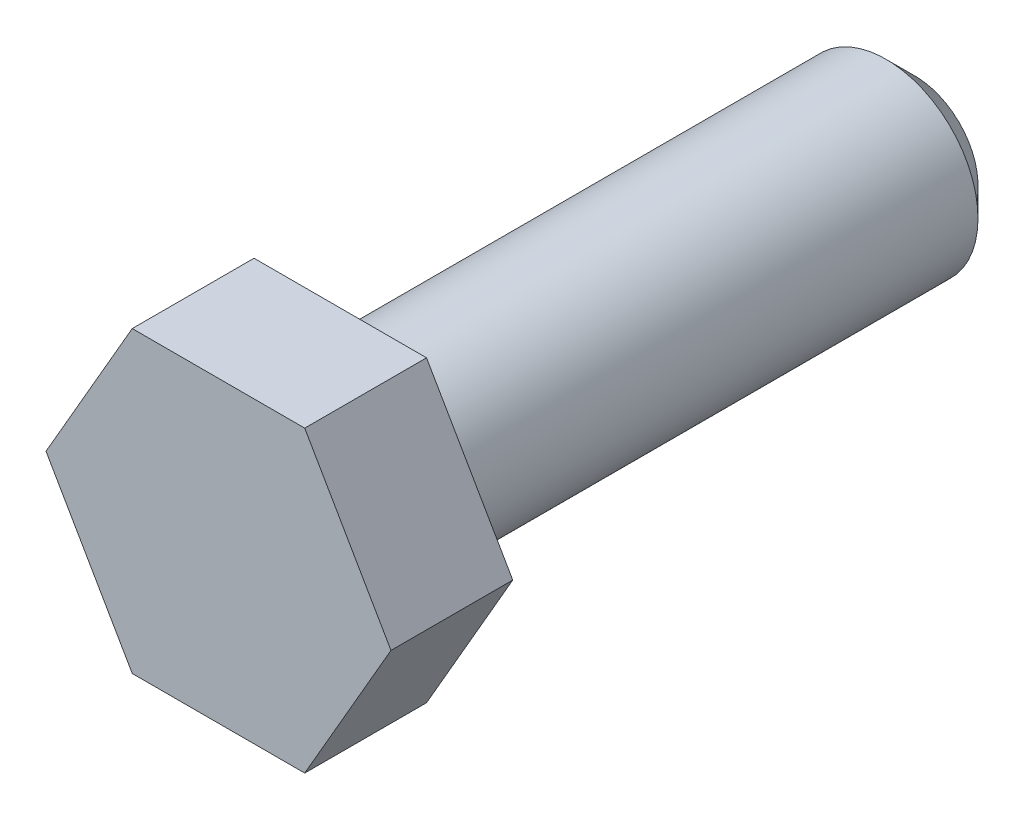
SolidWorks part; units mm, degrees
ref_plane "Plane1" through (0, 0, 0) normal (0, 0, 1) x (1, 0, 0)
ref_plane "MSC_PF1" through (0, 0, 0) normal (0, 1, 0) x (1, 0, 0)
ref_plane "Plane3" through (0, 0, 0) normal (1, 0, 0) x (0, 0, -1)
sketch "Sketch1" plane through (0, 0, 0) normal (0, 0, 1) x (1, 0, 0)
  line L0 (0, 0) -> (1, 0) construction
  line L1 (-3.7528, 6.5) -> (3.7528, 6.5)
  line L2 (-3.7528, -6.5) -> (3.7528, -6.5)
  line L3 (3.7528, 6.5) -> (7.5056, 0)
  line L4 (7.5056, 0) -> (3.7528, -6.5)
  line L5 (-3.7528, 6.5) -> (-7.5056, 0)
  line L6 (-7.5056, 0) -> (-3.7528, -6.5)
  circle A0 centre (0, 0) radius 6.5 construction
  dimension "P" = 1
  dimension "s" = 13
extrude "Base-Extrude" add sketch "Sketch1" along normal blind 5.3
sketch "Sketch3" plane through (0, 0, 0) normal (0, 0, -1) x (-1, 0, 0)
  circle A0 centre (0, 0) radius 4
  dimension "_d" = 8
extrude "Boss-Extrude1" add sketch "Sketch3" along normal blind 25
cosmetic thread "Условное изображение резьбы2" parameters "D2"=7
chamfer "Chamfer1" distance 1.25 angle 45 1 edges at (-4, 0, -25)
